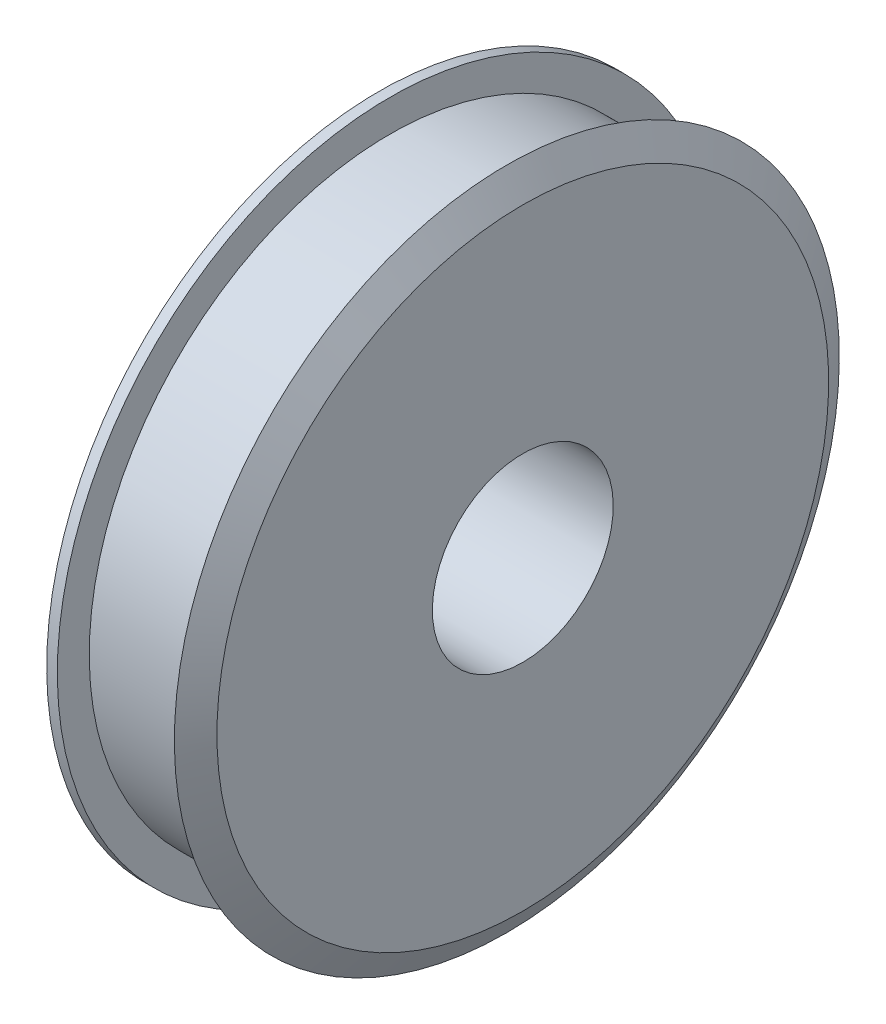
SolidWorks part; units mm, degrees
ref_plane "Plan de face" through (0, 0, 0) normal (0, 0, 1) x (1, 0, 0)
ref_plane "Plan de dessus" through (0, 0, 0) normal (0, 1, 0) x (1, 0, 0)
ref_plane "Plan de droite" through (0, 0, 0) normal (1, 0, 0) x (0, 0, -1)
sketch "Esquisse1" plane through (0, 0, 0) normal (0, 0, 1) x (1, 0, 0)
  line L0 (0, 0) -> (0, 62.5)
  line L2 (3, 57.5) -> (3, 0)
  line L3 (3, 0) -> (0, 0)
  line L4 (-22, 62.5) -> (-24, 62.5)
  line L5 (-24, 62.5) -> (-24, 0)
  line L6 (-24, 0) -> (-22, 0)
  line L7 (-22, 0) -> (-22, 62.5)
  line L8 (-24, 0) -> (3, 0) construction
  line L9 (0, 56.5) -> (-22, 56.5)
  line L11 (0, 62.5) -> (3, 57.5)
  point P12 (0, 0)
  point P13 (3, 60.9224)
  dimension "D1" = 3
  dimension "D2" = 2
  dimension "D3" = 22
  dimension "D4" = 115
  dimension "D5" = 125
  dimension "D6" = 6
revolve "Révolution1" add sketch "Esquisse1" angle 360 about L8
sketch "Esquisse2" plane through (-24, 0, 0) normal (-1, 0, 0) x (0, 0, 1)
  circle A0 centre (0, 0) radius 17
  dimension "D1" = 34
extrude "Enlèv. mat.-Extru.1" cut sketch "Esquisse2" against normal through all
